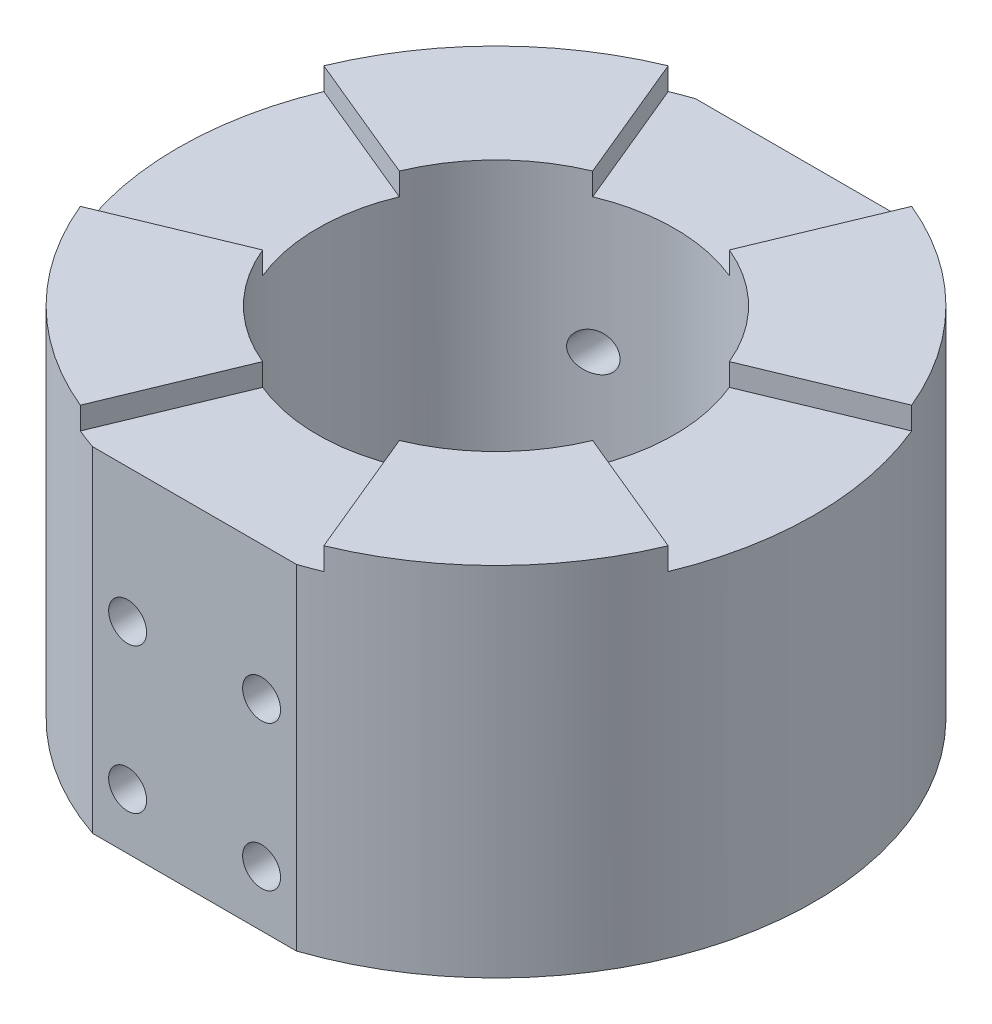
SolidWorks part; units mm, degrees
ref_plane "前视基准面" through (0, 0, 0) normal (0, 0, 1) x (1, 0, 0)
ref_plane "上视基准面" through (0, 0, 0) normal (0, 1, 0) x (1, 0, 0)
ref_plane "右视基准面" through (0, 0, 0) normal (1, 0, 0) x (0, 0, -1)
sketch "草图1" plane through (0, 0, 0) normal (0, 1, 0) x (1, 0, 0)
  circle A0 centre (0, 0) radius 142.5
  circle A1 centre (0, 0) radius 80
  dimension "D1" = 160
  dimension "D2" = 285
extrude "凸台-拉伸1" add sketch "草图1" along normal blind 160
sketch "草图2" plane through (0, 160, 0) normal (0, 1, 0) x (1, 0, 0)
  line L0 (0, 0) -> (0, 142.5) construction
  line L3 (0, 0) -> (-63.17, 152.5058) construction
  line L4 (-54.5324, 131.6528) -> (-30.6147, 73.9104)
  line L5 (54.5324, 131.6528) -> (30.6147, 73.9104)
  line L6 (0, 0) -> (62.7306, 151.445) construction
  circle A0 centre (0, 0) radius 80 construction
  circle A1 centre (0, 0) radius 142.5 construction
  arc A2 (30.6147, 73.9104) -> (-30.6147, 73.9104) centre (0, 0) ccw
  arc A3 (54.5324, 131.6528) -> (-54.5324, 131.6528) centre (0, 0) ccw
  dimension "D1" = 22.5
  dimension "D2" = 22.5
extrude "切除-拉伸1" cut sketch "草图2" against normal blind 10
pattern_circular "阵列(圆周)1" count 4 over 360 about axis through (0, 160, 0) along (0, -1, 0) of "切除-拉伸1"
sketch "草图3" plane through (0, 0, 0) normal (1, 0, 0) x (0, 0, -1)
  line L0 (0, 0) -> (0, 144.2241) construction
  line L1 (135, 0) -> (135, 166.8568)
  line L2 (-135, 0) -> (-135, 166.8568)
  line L3 (-135, 0) -> (-135, 144.2241) construction
  line L4 (135, 0) -> (135, 144.2241) construction
  line L5 (-135, 166.8568) -> (-157.8414, 166.8568)
  line L6 (-157.8414, 166.8568) -> (-157.8414, 0)
  line L7 (-157.8414, 0) -> (-135, 0)
  line L8 (135, 0) -> (152.8445, 0)
  line L9 (152.8445, 0) -> (152.8445, 166.8568)
  line L10 (152.8445, 166.8568) -> (135, 166.8568)
  dimension "D1" = 135
  dimension "D2" = 135
extrude "切除-拉伸2" cut sketch "草图3" against normal through all and the other way through all
sketch "草图4" plane through (0, 0, 135) normal (0, 0, 1) x (1, 0, 0)
  line L0 (0, 0) -> (0, 158.3328)
  line L1 (-45.6207, 0) -> (45.6207, 0) construction
  line L2 (-30, 25) -> (30, 25) construction
  line L3 (-30, 25) -> (-30, 90) construction
  circle A0 centre (-30, 25) radius 8.5
  circle A1 centre (30, 25) radius 8.5
  circle A2 centre (30, 90) radius 8.5
  circle A3 centre (-30, 90) radius 8.5
  point P7 (-27.9924, 89.969)
  point P8 (0, 0)
  dimension "D3" = 17
  dimension "D1" = 30
  dimension "D2" = 25
  dimension "D6" = 60
  dimension "D7" = 65
  dimension "D4" = 2
  dimension "D5" = 2
extrude "切除-拉伸3" cut sketch "草图4" against normal up to next contours A3 | A2 | A1 | A0
mirror "镜向1" about plane through (0, 0, 0) normal (0, 0, 1) of "切除-拉伸3"
